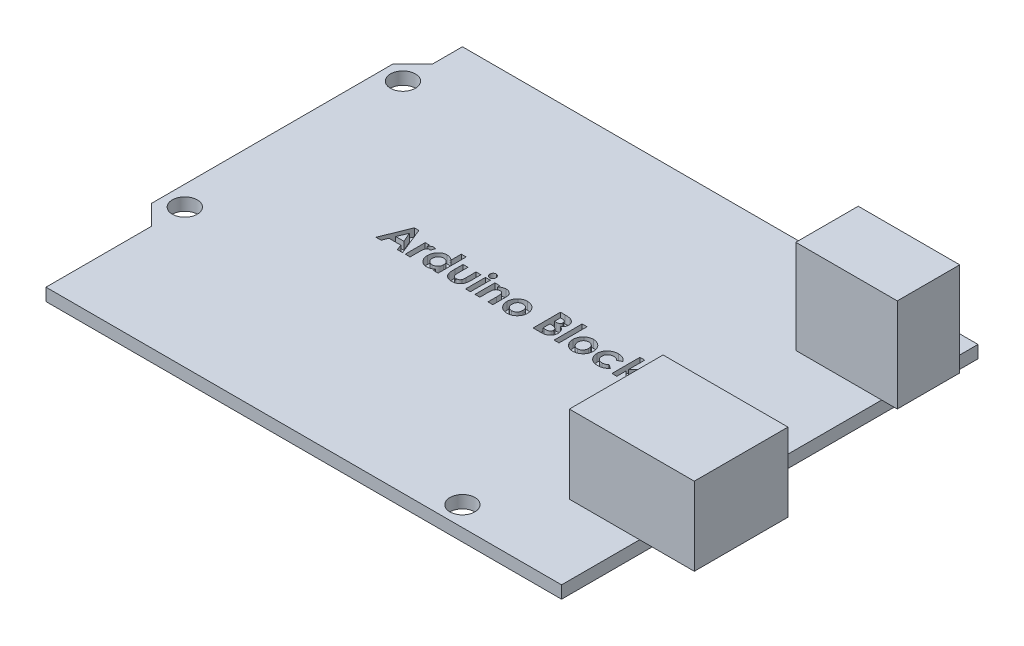
SolidWorks part; units mm, degrees
ref_plane "Front Plane" through (0, 0, 0) normal (0, 0, 1) x (1, 0, 0)
ref_plane "Top Plane" through (0, 0, 0) normal (0, 1, 0) x (1, 0, 0)
ref_plane "Right Plane" through (0, 0, 0) normal (1, 0, 0) x (0, 0, -1)
sketch "Sketch1" plane through (0, 0, 0) normal (0, 1, 0) x (1, 0, 0)
  line L1 (34.29, 26.67) -> (-34.29, 26.67)
  line L2 (34.29, 26.67) -> (34.29, -26.67)
  line L3 (34.29, -26.67) -> (-34.29, -26.67)
  line L4 (-34.29, 26.67) -> (-34.29, -26.67)
  line L5 (34.29, 26.67) -> (-34.29, -26.67) construction
  line L6 (34.29, -26.67) -> (-34.29, 26.67) construction
  point P0 (0, 0)
  dimension "D1" = 53.34
  dimension "D2" = 68.58
extrude "PCB" add sketch "Sketch1" along normal blind 1.6
sketch "Sketch2" plane through (0, 1.6, 0) normal (0, 1, 0) x (1, 0, 0)
  line L7 (23.29, 22.33) -> (36.29, 22.33)
  line L8 (23.29, 22.33) -> (23.29, 14.33)
  line L9 (23.29, 14.33) -> (36.29, 14.33)
  line L10 (36.29, 22.33) -> (36.29, 14.33)
  line L11 (23.29, 22.33) -> (36.29, 14.33) construction
  line L12 (23.29, 14.33) -> (36.29, 22.33) construction
  line L13 (-34.29, -26.67) -> (34.29, -26.67) construction
  line L14 (34.29, -26.67) -> (34.29, 26.67) construction
  point P5 (29.79, 18.33)
  dimension "D2" = 41
  dimension "D3" = 8
  dimension "D4" = 13
  dimension "D5" = 2
extrude "Charging Port" add sketch "Sketch2" along normal blind 12
sketch "Sketch4" plane through (0, 1.6, 0) normal (0, 1, 0) x (1, 0, 0)
  line L0 (-34.29, -26.67) -> (34.29, -26.67) construction
  line L1 (25.29, -4.67) -> (41.29, -4.67)
  line L2 (25.29, -4.67) -> (25.29, -16.67)
  line L3 (25.29, -16.67) -> (41.29, -16.67)
  line L4 (41.29, -4.67) -> (41.29, -16.67)
  line L5 (25.29, -4.67) -> (41.29, -16.67) construction
  line L6 (25.29, -16.67) -> (41.29, -4.67) construction
  line L7 (34.29, -26.67) -> (34.29, 14.33) construction
  point P0 (33.29, -10.67)
  dimension "D1" = 10
  dimension "D2" = 12
  dimension "D3" = 7
  dimension "D4" = 16
extrude "Ethernet" add sketch "Sketch4" along normal blind 10
sketch "Sketch5" plane through (0, 1.6, 0) normal (0, 1, 0) x (1, 0, 0)
  line L0 (-34.29, 0) -> (34.29, 0) construction
  line L1 (-34.29, 26.67) -> (-34.29, -26.67) construction
  line L2 (34.29, -4.67) -> (34.29, 14.33) construction
  text T0 "<b>Arduino Block</b>"
extrude "Cut-Extrude1" cut sketch "Sketch5" against normal blind 1
sketch "Sketch6" plane through (0, 1.6, 0) normal (0, 1, 0) x (1, 0, 0)
  line L0 (-31.75, 26.67) -> (-31.75, -26.67) construction
  line L1 (34.29, 26.67) -> (-34.29, 26.67) construction
  line L2 (-34.29, -26.67) -> (34.29, -26.67) construction
  line L3 (34.29, -4.67) -> (34.29, 14.33) construction
  line L4 (19.05, 26.67) -> (19.05, -26.67) construction
  line L5 (-31.75, 26.67) -> (-31.75, 22.8203)
  line L6 (-31.75, 22.8203) -> (-34.29, 20.2803)
  line L7 (-34.29, 26.67) -> (-34.29, -26.67) construction
  line L8 (-34.29, 20.2803) -> (-34.29, 26.67)
  line L9 (-34.29, 26.67) -> (-31.75, 26.67)
  line L10 (-34.29, -10.6135) -> (-31.75, -13.1535)
  line L11 (-31.75, -13.1535) -> (-31.75, -26.67)
  line L12 (-31.75, -26.67) -> (-34.29, -26.67)
  line L13 (-34.29, -26.67) -> (-34.29, -10.6135)
  circle A0 centre (-31.75, 19.05) radius 1.6
  circle A1 centre (-31.75, -8.89) radius 1.6
  circle A2 centre (19.05, -24.13) radius 1.6
  circle A3 centre (19.05, 24.13) radius 1.6
  point P8 (-31.75, -8.89)
  point P9 (-31.75, 19.05)
  point P16 (19.05, -24.13)
  point P19 (19.05, -24.13)
  dimension "D4" = 3.2
  dimension "D5" = 3.2
  dimension "D8" = 3.2
  dimension "D10" = 3.2
  dimension "D1" = 66.04
  dimension "D2" = 17.78
  dimension "D3" = 45.72
  dimension "D6" = 15.24
  dimension "D7" = 2.54
  dimension "D9" = 2.54
extrude "Cut-Extrude2" cut sketch "Sketch6" against normal through all
